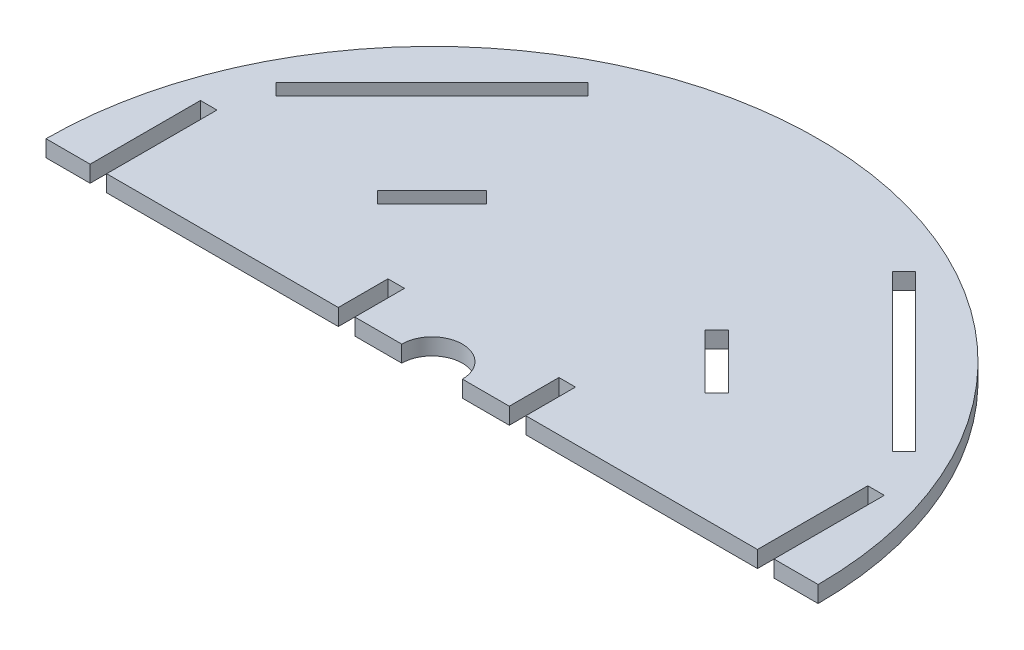
SolidWorks part; units mm, degrees
ref_plane "Alzado" through (0, 0, 0) normal (0, 0, 1) x (1, 0, 0)
ref_plane "Planta" through (0, 0, 0) normal (0, 1, 0) x (1, 0, 0)
ref_plane "Vista lateral" through (0, 0, 0) normal (1, 0, 0) x (0, 0, -1)
sketch "Croquis1" plane through (0, 0, 0) normal (0, 1, 0) x (1, 0, 0)
  line L0 (24.7487, 24.7487) -> (29.6985, 19.799)
  line L1 (29.6985, 19.799) -> (31.8198, 21.9203)
  line L2 (31.8198, 21.9203) -> (21.9203, 31.8198)
  line L3 (19.799, 29.6985) -> (21.9203, 31.8198)
  line L4 (24.7487, 24.7487) -> (19.799, 29.6985)
  line L5 (-59, 0) -> (-17, 0)
  line L6 (-14, 0) -> (-5.5, 0)
  line L7 (5.5, 0) -> (14, 0)
  line L8 (17, 0) -> (59, 0)
  line L9 (62, 0) -> (70, 0)
  line L10 (-3.8891, 3.8891) -> (-24.7487, 24.7487) construction
  line L11 (-24.7487, 24.7487) -> (-19.799, 29.6985)
  line L12 (-19.799, 29.6985) -> (-21.9203, 31.8198)
  line L19 (-70, 0) -> (-62, 0)
  line L20 (-14, 0) -> (-14, 9)
  line L21 (-14, 9) -> (-17, 9)
  line L22 (-17, 9) -> (-17, 0)
  line L23 (-21.9203, 31.8198) -> (-31.8198, 21.9203)
  line L24 (-24.7487, 24.7487) -> (-29.6985, 19.799)
  line L25 (-29.6985, 19.799) -> (-31.8198, 21.9203)
  line L35 (14, 9) -> (14, 0)
  line L36 (17, 9) -> (14, 9)
  line L37 (17, 0) -> (17, 9)
  line L47 (55.8614, 27.5772) -> (27.5772, 55.8614)
  line L48 (27.5772, 55.8614) -> (29.6985, 57.9828)
  line L49 (29.6985, 57.9828) -> (43.8406, 43.8406)
  line L50 (43.8406, 43.8406) -> (57.9828, 29.6985)
  line L51 (57.9828, 29.6985) -> (55.8614, 27.5772)
  line L52 (59, 0) -> (59, 20)
  line L53 (59, 20) -> (62, 20)
  line L54 (62, 20) -> (62, 0)
  line L72 (-59, 20) -> (-59, 0)
  line L75 (-62, 0) -> (-62, 20)
  line L76 (-62, 20) -> (-59, 20)
  line L77 (-27.5772, 55.8614) -> (-55.8614, 27.5772)
  line L78 (-55.8614, 27.5772) -> (-57.9828, 29.6985)
  line L79 (-57.9828, 29.6985) -> (-43.8406, 43.8406)
  line L80 (-43.8406, 43.8406) -> (-29.6985, 57.9828)
  line L81 (-29.6985, 57.9828) -> (-27.5772, 55.8614)
  line L85 (9, 14) -> (9, 17) [skipped]
  line L86 (0, 14) -> (9, 14) [skipped]
  line L87 (9, 17) -> (-9, 17) [skipped]
  line L90 (14, 0) -> (14, -9) [skipped]
  line L91 (24.7487, -24.7487) -> (19.799, -29.6985) [skipped]
  line L92 (19.799, -29.6985) -> (21.9203, -31.8198) [skipped]
  line L93 (21.9203, -31.8198) -> (31.8198, -21.9203) [skipped]
  line L94 (29.6985, -19.799) -> (31.8198, -21.9203) [skipped]
  line L95 (24.7487, -24.7487) -> (29.6985, -19.799) [skipped]
  line L96 (-24.7487, -24.7487) -> (-29.6985, -19.799) [skipped]
  line L97 (-29.6985, -19.799) -> (-31.8198, -21.9203) [skipped]
  line L98 (-31.8198, -21.9203) -> (-21.9203, -31.8198) [skipped]
  line L99 (-19.799, -29.6985) -> (-21.9203, -31.8198) [skipped]
  line L100 (-24.7487, -24.7487) -> (-19.799, -29.6985) [skipped]
  line L101 (14, -9) -> (17, -9) [skipped]
  line L102 (-9, -14) -> (-9, -17) [skipped]
  line L103 (0, -14) -> (-9, -14) [skipped]
  line L105 (-9, -17) -> (9, -17) [skipped]
  arc A0 (5.5, 0) -> (-5.5, 0) centre (0, 0) ccw
  arc A2 (70, 0) -> (-70, 0) centre (0, 0) ccw
  point P26 (0, 0)
  point P47 (0, 0)
  point P88 (0, 0)
  point P92 (0, 0)
  dimension "D2" = 7
  dimension "D5" = 4
  dimension "D9" = 7
  dimension "D10" = 3
  dimension "D12" = 3
  dimension "D14" = 4
extrude "Saliente-Extruir1" add sketch "Croquis1" along normal blind 3
